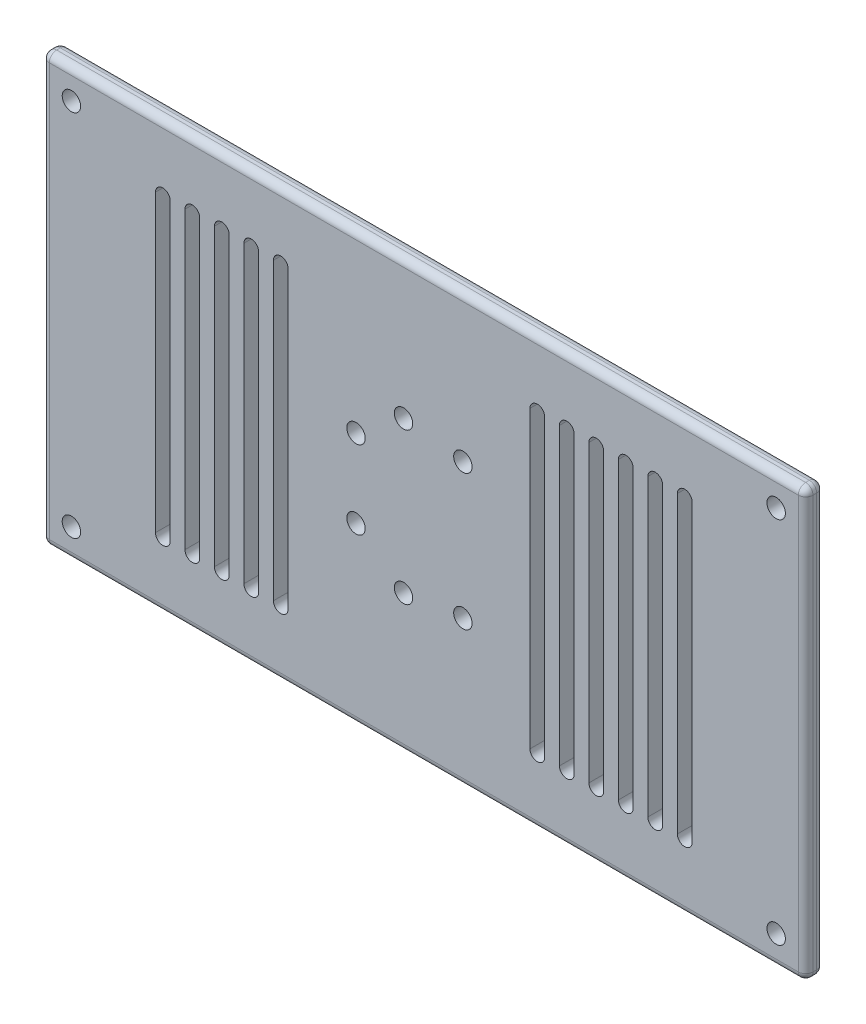
SolidWorks part; units mm, degrees
ref_plane "Plan de face" through (0, 0, 0) normal (0, 0, 1) x (1, 0, 0)
ref_plane "Plan de dessus" through (0, 0, 0) normal (0, 1, 0) x (1, 0, 0)
ref_plane "Plan de droite" through (0, 0, 0) normal (1, 0, 0) x (0, 0, -1)
sketch "Esquisse1" plane through (0, 0, 0) normal (0, 0, 1) x (1, 0, 0)
  line L1 (-51.8, 29) -> (51.8, 29)
  line L2 (-51.8, 29) -> (-51.8, -29)
  line L3 (-51.8, -29) -> (51.8, -29)
  line L4 (51.8, 29) -> (51.8, -29)
  line L5 (-51.8, 29) -> (51.8, -29) construction
  line L6 (-51.8, -29) -> (51.8, 29) construction
  point P0 (0, 0)
  point P5 (0, 0)
  point P13 (0, 0)
  dimension "D1" = 58
  dimension "D2" = 103.6
extrude "Boss.-Extru.1" add sketch "Esquisse1" along normal blind 2.5
sketch "Esquisse3" plane through (0, 0, 2.5) normal (0, 0, 1) x (1, 0, 0)
  line L0 (51.8, 29) -> (-51.8, 29) construction
  line L1 (-51.8, 29) -> (-51.8, -29) construction
  line L2 (-51.8, -29) -> (51.8, -29) construction
  line L3 (51.8, -29) -> (51.8, 29) construction
  circle A0 centre (-47.8, 25) radius 3
  circle A1 centre (47.8, 25) radius 3
  circle A2 centre (-47.8, -25) radius 3
  circle A3 centre (47.8, -25) radius 3
  point P17 (-47.8, 25)
  point P18 (-47.8, -25)
  point P19 (47.8, -25)
  point P20 (47.8, 25)
  dimension "D3" = 4
  dimension "D1" = 4
  dimension "D2" = 4
  dimension "D4" = 4
  dimension "D5" = 4
  dimension "D6" = 4
  dimension "D7" = 4
  dimension "D8" = 4
sketch "Esquisse17" plane through (0, 0, 2.5) normal (0, 0, 1) x (1, 0, 0)
  line L1 (-2.75, 10.25) -> (2.75, 10.25)
  line L2 (-2.75, 10.25) -> (-2.75, -10.25) construction
  line L3 (-2.75, -10.25) -> (2.75, -10.25)
  line L4 (2.75, 10.25) -> (2.75, -10.25)
  line L5 (-2.75, 10.25) -> (2.75, -10.25) construction
  line L6 (-2.75, -10.25) -> (2.75, 10.25) construction
  circle A0 centre (-2.75, 10.25) radius 3
  circle A1 centre (-2.75, -10.25) radius 3
  point P0 (0, 0)
  point P9 (-2.75, -10.25)
  point P10 (-2.75, 10.25)
  dimension "D1" = 20.5
  dimension "D2" = 5.5
fillet "Congé3" radius 1 12 edges at (-51.8, 0, 2.5) (0, -29, 2.5) (0, 29, 2.5) (51.8, 0, 2.5) (51.8, -29, 1.25) (51.8, 29, 1.25) (-51.8, 29, 1.25) (-51.8, -29, 1.25) (51.8, 0, 0) (0, 29, 0) (-51.8, 0, 0) (0, -29, 0)
sketch "Esquisse32" plane through (0, 0, 2.5) normal (0, 0, 1) x (1, 0, 0)
  line L1 (5.3033, 9.1924) -> (9.1924, 5.3033)
  line L2 (5.3033, 9.1924) -> (-9.1924, -5.3033)
  line L3 (-9.1924, -5.3033) -> (-5.3033, -9.1924)
  line L4 (9.1924, 5.3033) -> (-5.3033, -9.1924)
  line L5 (-2.75, 10.25) -> (2.75, -10.25) construction
  line L6 (-2.75, -10.25) -> (2.75, 10.25) construction
  circle A0 centre (5.3033, 9.1924) radius 3
  circle A1 centre (-9.1924, -5.3033) radius 3
  point P0 (0, 0)
extrude "Boss.-Extru.8" add sketch "Esquisse32" against normal blind 7 contours A1 | A0
sketch "Esquisse26" plane through (0, 0, 2.5) normal (0, 0, 1) x (1, 0, 0)
  line L1 (5.3033, -9.1924) -> (9.1924, -5.3033)
  line L2 (5.3033, -9.1924) -> (-9.1924, 5.3033)
  line L3 (-9.1924, 5.3033) -> (-5.3033, 9.1924)
  line L4 (9.1924, -5.3033) -> (-5.3033, 9.1924)
  line L5 (5.3033, -9.1924) -> (-5.3033, 9.1924) construction
  line L6 (-9.1924, 5.3033) -> (9.1924, -5.3033) construction
  circle A0 centre (-9.1924, 5.3033) radius 3
  circle A1 centre (5.3033, -9.1924) radius 3
  point P0 (0, 0)
  dimension "D1" = 5.5
  dimension "D2" = 20.5
extrude "Boss.-Extru.10" add sketch "Esquisse26" against normal blind 7 contours A1 | A0
extrude "Boss.-Extru.7" add sketch "Esquisse17" against normal blind 7 contours A0 | A1
hole_wizard "Trou pour taraudage pour trou taraudé M37" positions "Esquisse3D9" profile "Esquisse25" hole size "M3" standard "AS"
sketch3d "Esquisse3D9"
  point P0 (-2.75, -10.25, 2.5)
  point P3 (-2.75, 10.25, 2.5)
sketch "Esquisse25" plane through (-2.75, -10.25, 2.5) normal (1, 0, 0) x (0, -1, 0)
  line L0 (0, 0) -> (0, 5.7511)
  line L1 (0, 5.7511) -> (1.25, 5)
  line L2 (1.25, 5) -> (1.25, 0)
  line L5 (1.25, 0) -> (0, 0)
  line L10 (0, 5.7511) -> (-1.25, 5) construction
  line L11 (0, -6.35) -> (0, 107.95) construction
  dimension "Diamètre du perçage" = 2.5
  dimension "Profondeur du perçage" = 5
  dimension "Angle de pointe" = 118
hole_wizard "Trou pour taraudage pour trou taraudé M39" positions "Esquisse3D13" profile "Esquisse31" hole size "M3" standard "AS"
sketch3d "Esquisse3D13"
  point P0 (-9.1924, 5.3033, 2.5)
  point P3 (5.3033, -9.1924, 2.5)
sketch "Esquisse31" plane through (-9.1924, 5.3033, 2.5) normal (1, 0, 0) x (0, -1, 0)
  line L0 (0, 0) -> (0, 5.7511)
  line L1 (0, 5.7511) -> (1.25, 5)
  line L2 (1.25, 5) -> (1.25, 0)
  line L5 (1.25, 0) -> (0, 0)
  line L10 (0, 5.7511) -> (-1.25, 5) construction
  line L11 (0, -6.35) -> (0, 107.95) construction
  dimension "Diamètre du perçage" = 2.5
  dimension "Profondeur du perçage" = 5
  dimension "Angle de pointe" = 118
hole_wizard "Trou pour taraudage pour trou taraudé M310" positions "Esquisse3D14" profile "Esquisse33" hole size "M3" standard "AS"
sketch3d "Esquisse3D14"
  point P0 (5.3033, 9.1924, 2.5)
  point P3 (-9.1924, -5.3033, 2.5)
sketch "Esquisse33" plane through (5.3033, 9.1924, 2.5) normal (1, 0, 0) x (0, -1, 0)
  line L0 (0, 0) -> (0, 5.7511)
  line L1 (0, 5.7511) -> (1.25, 5)
  line L2 (1.25, 5) -> (1.25, 0)
  line L5 (1.25, 0) -> (0, 0)
  line L10 (0, 5.7511) -> (-1.25, 5) construction
  line L11 (0, -6.35) -> (0, 107.95) construction
  dimension "Diamètre du perçage" = 2.5
  dimension "Profondeur du perçage" = 5
  dimension "Angle de pointe" = 118
fillet "Congé5" radius 0.5 12 edges at (8.3033, -9.1924, -4.5) (0.25, -10.25, -4.5) (-6.1924, -5.3033, -4.5) (-6.1924, 5.3033, -4.5) (8.3033, 9.1924, -4.5) (0.25, 10.25, -4.5) (8.3033, 9.1924, 0) (0.25, 10.25, 0) (-6.1924, 5.3033, 0) (-6.1924, -5.3033, 0) (0.25, -10.25, 0) (8.3033, -9.1924, 0)
hole_wizard "Trou pour taraudage pour trou taraudé M311" positions "Esquisse3D15" profile "Esquisse34" hole size "M3" standard "AS"
sketch3d "Esquisse3D15"
  point P0 (47.8, 25, 2.5)
  point P3 (47.8, -25, 2.5)
  point P6 (-47.8, -25, 2.5)
  point P9 (-47.8, 25, 2.5)
sketch "Esquisse34" plane through (47.8, 25, 2.5) normal (1, 0, 0) x (0, -1, 0)
  line L0 (0, 0) -> (0, 5.7511)
  line L1 (0, 5.7511) -> (1.25, 5)
  line L2 (1.25, 5) -> (1.25, 0)
  line L5 (1.25, 0) -> (0, 0)
  line L10 (0, 5.7511) -> (-1.25, 5) construction
  line L11 (0, -6.35) -> (0, 107.95) construction
  dimension "Diamètre du perçage" = 2.5
  dimension "Profondeur du perçage" = 5
  dimension "Angle de pointe" = 118
sketch "Esquisse36" plane through (0, 0, 2.5) normal (0, 0, 1) x (1, 0, 0)
  line L0 (25.4, 0) -> (0, 0) construction
  line L1 (50.8, -28) -> (50.8, 28) construction
  line L2 (50.8, 0) -> (25.4, 0) construction
  line L4 (35.4, -20) -> (15.4, -20) construction
  line L5 (35.4, -20) -> (35.4, 20) construction
  line L6 (35.4, 20) -> (15.4, 20) construction
  line L7 (15.4, -20) -> (15.4, 20) construction
  line L8 (35.4, -20) -> (15.4, 20) construction
  line L9 (35.4, 20) -> (15.4, -20) construction
  line L10 (35.4, 20) -> (35.4, -20) construction
  line L11 (36.4, 20) -> (36.4, -20)
  line L12 (34.4, 20) -> (34.4, -20)
  arc A0 (36.4, 20) -> (34.4, 20) centre (35.4, 20) ccw
  arc A1 (34.4, -20) -> (36.4, -20) centre (35.4, -20) ccw
  point P0 (25.4, 0)
  point P8 (35.4, 0)
  dimension "D1" = 20
  dimension "D2" = 40
extrude "Enlèv. mat.-Extru.2" cut sketch "Esquisse36" against normal through all
pattern_linear "Répétition linéaire1" count 6 spacing 4 along (-1, 0, 0) of "Enlèv. mat.-Extru.2"
sketch "Esquisse37" plane through (0, 0, 2.5) normal (0, 0, 1) x (1, 0, 0)
  line L0 (0, 0) -> (-50.8, 0) construction
  line L1 (-50.8, 28) -> (-50.8, -28) construction
  line L2 (-35.4, 20) -> (-35.4, -20) construction
  line L3 (-15.4, 20) -> (-35.4, 20) construction
  line L4 (-15.4, 20) -> (-15.4, -20) construction
  line L5 (-15.4, -20) -> (-35.4, -20) construction
  line L6 (-35.4, 20) -> (-35.4, -20) construction
  line L7 (-15.4, 20) -> (-35.4, -20) construction
  line L8 (-15.4, -20) -> (-35.4, 20) construction
  line L9 (-34.4, 20) -> (-34.4, -20)
  line L10 (-36.4, 20) -> (-36.4, -20)
  arc A0 (-34.4, 20) -> (-36.4, 20) centre (-35.4, 20) ccw
  arc A1 (-36.4, -20) -> (-34.4, -20) centre (-35.4, -20) ccw
  point P5 (-25.4, 0)
  point P11 (-35.4, 0)
  dimension "D1" = 40
  dimension "D2" = 20
extrude "Enlèv. mat.-Extru.3" cut sketch "Esquisse37" against normal through all
pattern_linear "Répétition linéaire2" count 5 spacing 4 along (1, 0, 0) of "Enlèv. mat.-Extru.3"
